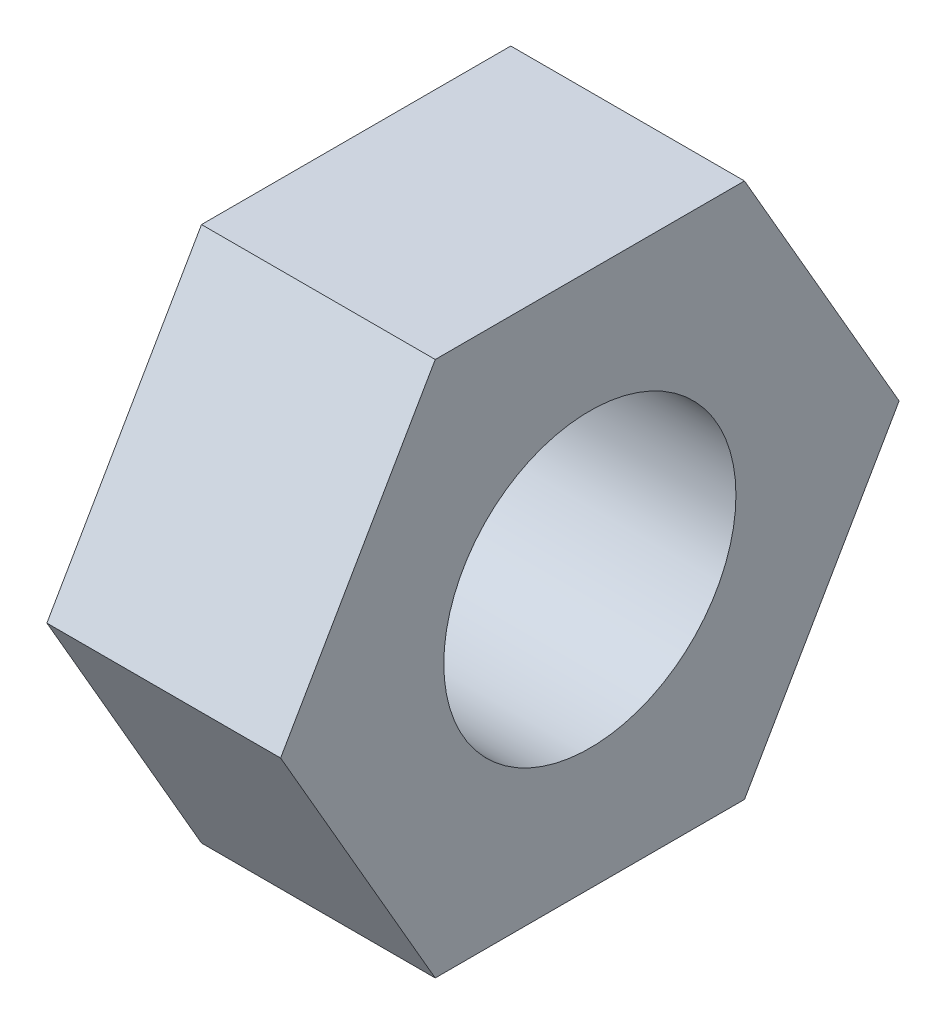
SolidWorks part; units mm, degrees
other "Preload Thrust Plate M3 Nut"
ref_plane "Front Plane" through (0, 0, 0) normal (0, 0, 1) x (1, 0, 0)
ref_plane "Top Plane" through (0, 0, 0) normal (0, 1, 0) x (1, 0, 0)
ref_plane "Right Plane" through (0, 0, 0) normal (1, 0, 0) x (0, 0, -1)
sketch3d "M3 nut blank sketch datum points"
  point P0 (20.7, -38, -11.5)
  point P1 (20.7, -28, -11.5)
  point P2 (20.7, -38, -1.5)
ref_plane "M3 nut blank sketch plane" through (20.7, 0, 0) normal (1, 0, 0) x (0, 0, -1)
sketch "M3 nut blank sketch" plane through (20.7, 0, 0) normal (1, 0, 0) x (0, 0, -1)
  line L0 (9.9123, -35.25) -> (8.3246, -38)
  line L1 (8.3246, -38) -> (9.9123, -40.75)
  line L2 (9.9123, -40.75) -> (13.0877, -40.75)
  line L3 (13.0877, -40.75) -> (14.6754, -38)
  line L4 (14.6754, -38) -> (13.0877, -35.25)
  line L5 (13.0877, -35.25) -> (9.9123, -35.25)
  circle A0 centre (11.5, -38) radius 3.1754 construction
extrude "M3 nut blank" add sketch "M3 nut blank sketch" along normal blind 2.4 separate body
sketch3d "M3 thread envelope sketch datum points"
  point P0 (20.6, -38, -11.5)
  point P1 (20.6, -28, -11.5)
  point P2 (20.6, -38, -1.5)
ref_plane "M3 thread envelope sketch plane" through (20.6, 0, 0) normal (1, 0, 0) x (0, 0, -1)
sketch "M3 thread envelope sketch" plane through (20.6, 0, 0) normal (1, 0, 0) x (0, 0, -1)
  circle A0 centre (11.5, -38) radius 1.5
extrude "M3 thread envelope" cut sketch "M3 thread envelope sketch" along normal blind 2.6
